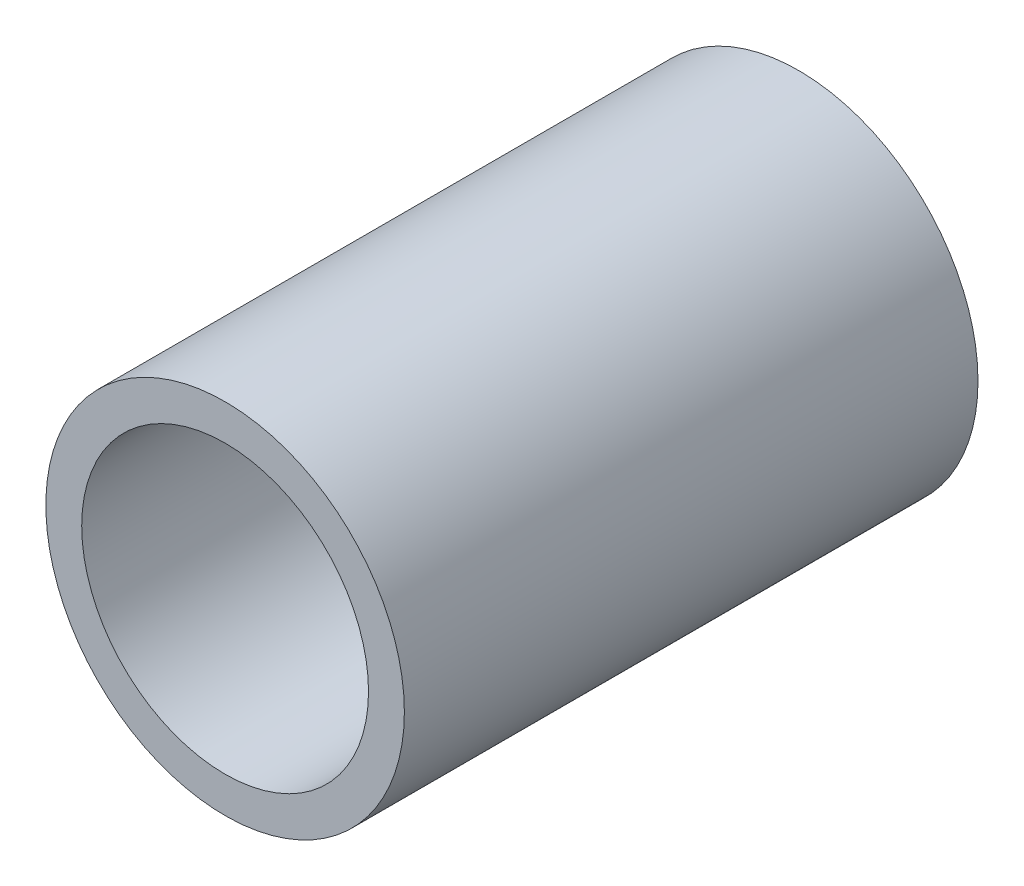
SolidWorks part; units mm, degrees
ref_plane "Front Plane" through (0, 0, 0) normal (0, 0, 1) x (1, 0, 0)
ref_plane "Top Plane" through (0, 0, 0) normal (0, 1, 0) x (1, 0, 0)
ref_plane "Right Plane" through (0, 0, 0) normal (1, 0, 0) x (0, 0, -1)
sketch "Sketch1" plane through (0, 0, 0) normal (0, 0, 1) x (1, 0, 0)
  circle A0 centre (0, 0) radius 3.175
  circle A1 centre (0, 0) radius 3.9688
  dimension "D1" = 6.35
  dimension "D2" = 7.9375
extrude "Extrude1" add sketch "Sketch1" along normal mid plane 12.7
